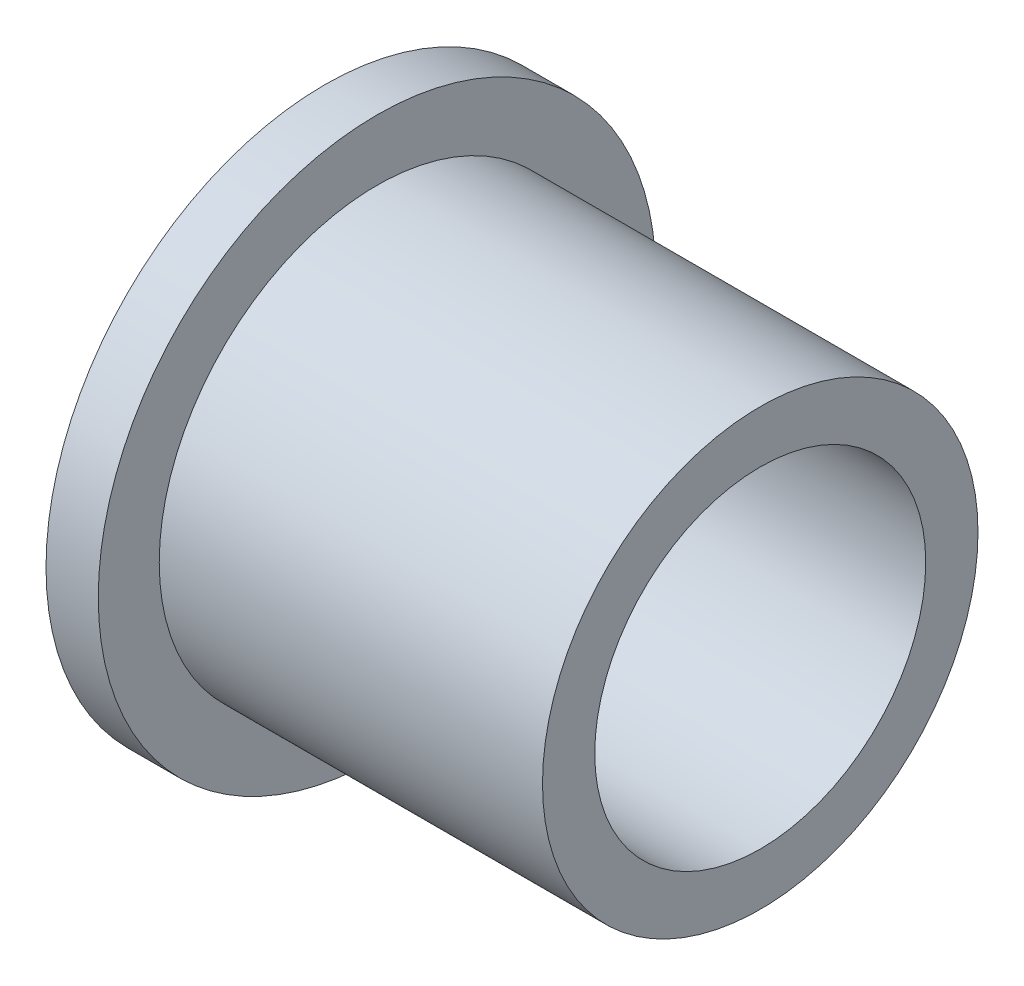
SolidWorks part; units mm, degrees
ref_plane "Front Plane" through (0, 0, 0) normal (0, 0, 1) x (1, 0, 0)
ref_plane "Top Plane" through (0, 0, 0) normal (0, 1, 0) x (1, 0, 0)
ref_plane "Right Plane" through (0, 0, 0) normal (1, 0, 0) x (0, 0, -1)
sketch "Sketch1" plane through (0, 0, 0) normal (0, 0, 1) x (1, 0, 0)
  line L0 (-38.1905, 0) -> (39.5238, 0) construction
  line L1 (0, 0) -> (0, 16)
  line L2 (0, 16) -> (3, 16)
  line L3 (3, 16) -> (3, 12.5)
  line L4 (3, 12.5) -> (25, 12.5)
  line L5 (25, 12.5) -> (25, 0)
  line L9 (25, 0) -> (0, 0)
  point P5 (0, 8)
  dimension "D1" = 16
  dimension "D2" = 12.5
  dimension "D3" = 25
  dimension "D4" = 22
revolve "Revolve2" add sketch "Sketch1" angle 360 about L0
sketch "Sketch2" plane through (25, 0, 0) normal (1, 0, 0) x (0, 0, -1)
  circle A0 centre (0, 0) radius 9.5
  circle A1 centre (0, 0) radius 12.5 construction
  dimension "D1" = 3
extrude "Cut-Extrude1" cut sketch "Sketch2" against normal through all
